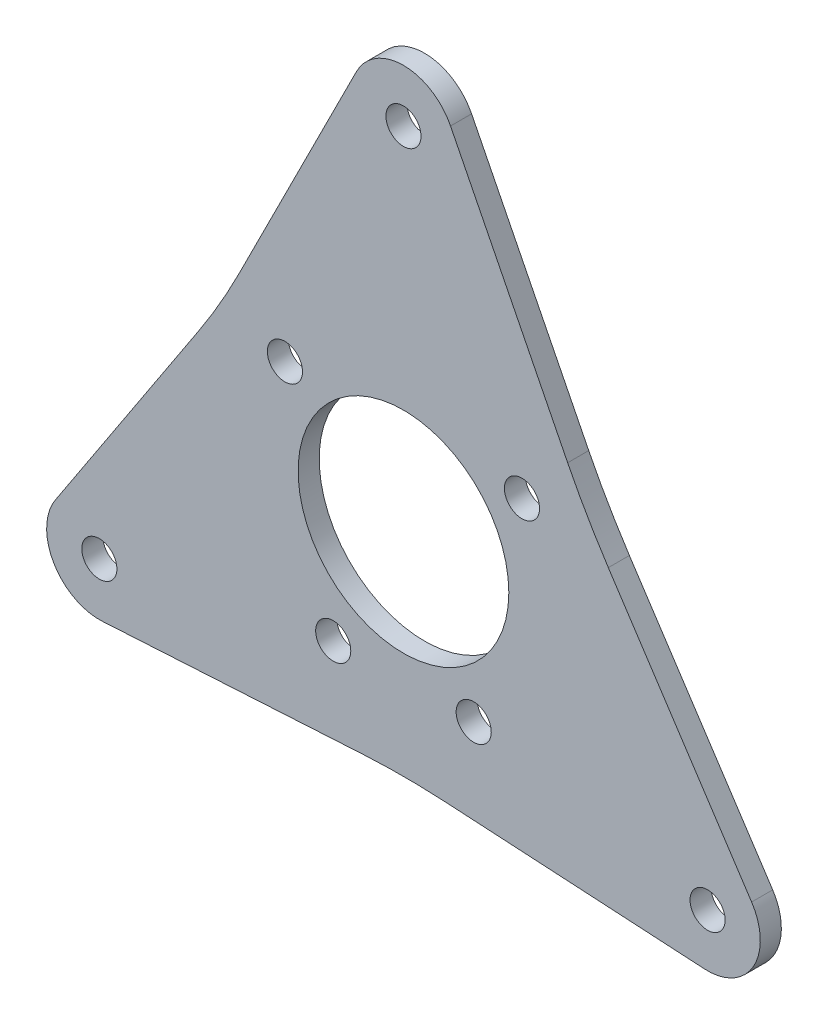
SolidWorks part; units mm, degrees
ref_plane "Front Plane" through (0, 0, 0) normal (0, 0, 1) x (1, 0, 0)
ref_plane "Top Plane" through (0, 0, 0) normal (0, 1, 0) x (1, 0, 0)
ref_plane "Right Plane" through (0, 0, 0) normal (1, 0, 0) x (0, 0, -1)
sketch "Sketch1" plane through (0, 0, 0) normal (0, 0, 1) x (1, 0, 0)
  line L0 (33.75, 25.0611) -> (-33.75, 25.0611) construction
  line L1 (0, 0) -> (0, 51.7411) construction
  line L2 (-99.1366, -41.7601) -> (-58.3366, 20.3026)
  line L3 (-46.7508, 40.3697) -> (-13.403, 106.7349)
  line L4 (13.403, 106.7349) -> (46.7508, 40.3697)
  line L5 (58.3366, 20.3026) -> (99.1366, -41.7601)
  line L6 (0, 0) -> (-81.3002, 46.9387) construction
  line L7 (-85.7336, -64.9748) -> (-11.5858, -60.6723)
  line L8 (11.5858, -60.6723) -> (85.7336, -64.9748)
  line L9 (-33.75, 25.0611) -> (20, -36.9324) construction
  line L10 (-20, -36.9324) -> (20, -36.9324) construction
  line L11 (33.75, 25.0611) -> (-20, -36.9324) construction
  line L12 (0, 0) -> (-20, -36.9324) construction
  circle A0 centre (0, 100) radius 5
  circle A1 centre (86.6025, -50) radius 5
  circle A2 centre (-86.6025, -50) radius 5
  circle A7 centre (0, 0) radius 30
  arc A8 (13.403, 106.7349) -> (-13.403, 106.7349) centre (0, 100) ccw
  arc A9 (85.7336, -64.9748) -> (99.1366, -41.7601) centre (86.6025, -50) ccw
  arc A10 (-99.1366, -41.7601) -> (-85.7336, -64.9748) centre (-86.6025, -50) ccw
  arc A11 (46.7508, 40.3697) -> (58.3366, 20.3026) centre (225.458, 130.1682) ccw
  arc A12 (-58.3366, 20.3026) -> (-46.7508, 40.3697) centre (-225.458, 130.1682) ccw
  arc A13 (-11.5858, -60.6723) -> (11.5858, -60.6723) centre (0, -260.3364) cw
  circle A14 centre (0, 0) radius 67 construction
  circle A15 centre (-33.75, 25.0611) radius 5
  circle A16 centre (33.75, 25.0611) radius 5
  circle A17 centre (-20, -36.9324) radius 5
  circle A18 centre (20, -36.9324) radius 5
  point P2 (0, 25.0611)
  point P10 (0, 0)
  point P21 (0, 0)
  point P30 (0, -60)
  point P40 (51.9615, 30)
  point P43 (-51.9615, 30)
  point P51 (0, -36.9324)
  dimension "D1" = 10
  dimension "D4" = 42
  dimension "D8" = 60
  dimension "D9" = 30
  dimension "D11" = 200
  dimension "D12" = 200
  dimension "D15" = 10
  dimension "D2" = 100
  dimension "D10" = 60
  dimension "D13" = 60
  dimension "D14" = 60
  dimension "D16" = 67.5
  dimension "D17" = 40
  dimension "D18" = 63.5
  dimension "D3" = 3
extrude "Boss-Extrude1" add sketch "Sketch1" along normal blind 6
